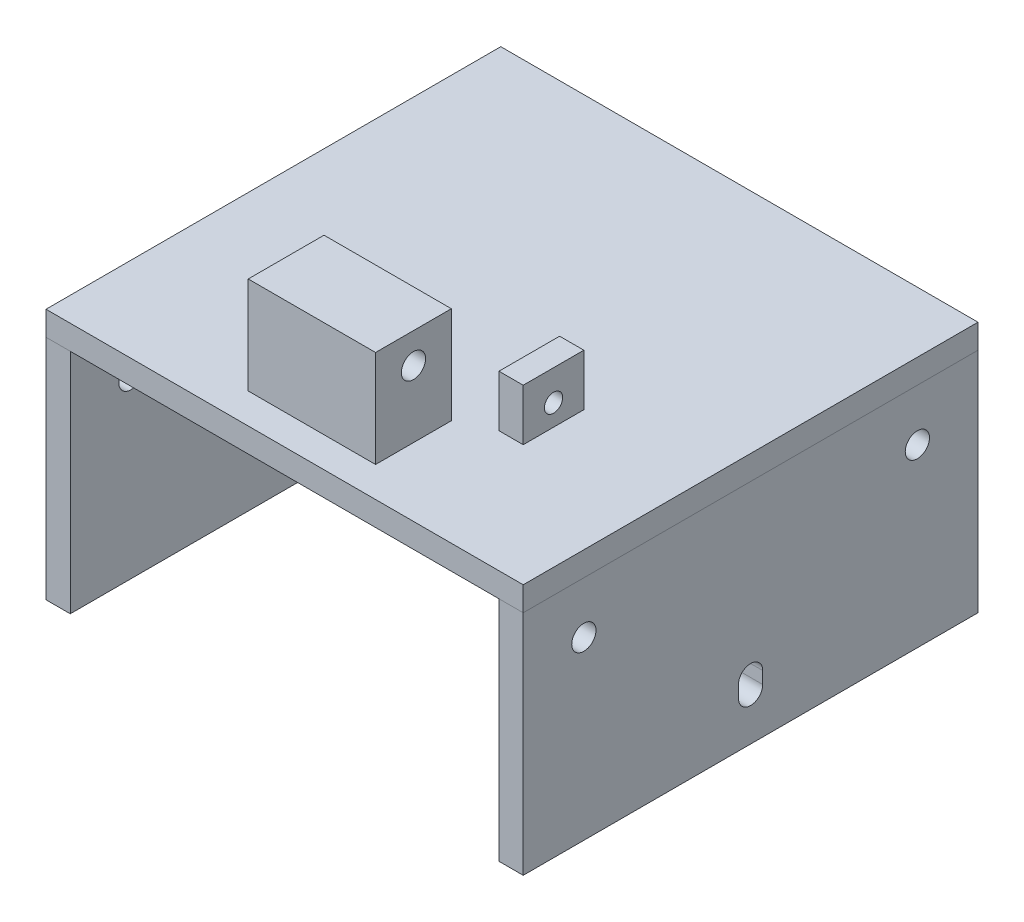
SolidWorks part; units mm, degrees
ref_plane "Front Plane" through (0, 0, 0) normal (0, 0, 1) x (1, 0, 0)
ref_plane "Top Plane" through (0, 0, 0) normal (0, 1, 0) x (1, 0, 0)
ref_plane "Right Plane" through (0, 0, 0) normal (1, 0, 0) x (0, 0, -1)
sketch "Sketch1" plane through (0, 0, 0) normal (0, 0, 1) x (1, 0, 0)
  line L1 (-78.7, -4) -> (78.7, -4)
  line L2 (-78.7, -4) -> (-78.7, 4)
  line L3 (-78.7, 4) -> (78.7, 4)
  line L4 (78.7, -4) -> (78.7, 4)
  line L5 (-78.7, -4) -> (78.7, 4) construction
  line L6 (-78.7, 4) -> (78.7, -4) construction
  point P0 (0, 0)
  dimension "D1" = 8
  dimension "D2" = 157.4
extrude "Boss-Extrude1" add sketch "Sketch1" along normal blind 150
sketch "Sketch2" plane through (0, -4, 0) normal (0, -1, 0) x (1, 0, 0)
  line L0 (-78.7, 0) -> (78.7, 0) construction
  line L1 (-78.7, 150) -> (-70.7, 150)
  line L2 (-78.7, 150) -> (-78.7, 0)
  line L3 (-78.7, 0) -> (-70.7, 0)
  line L4 (-70.7, 150) -> (-70.7, 0)
  line L5 (-78.7, 150) -> (78.7, 150) construction
  line L6 (78.7, 0) -> (70.7, 0)
  line L7 (78.7, 0) -> (78.7, 150)
  line L8 (78.7, 150) -> (70.7, 150)
  line L9 (70.7, 0) -> (70.7, 150)
  dimension "D1" = 8
  dimension "D2" = 8
extrude "Boss-Extrude2" add sketch "Sketch2" along normal blind 75 separate body
sketch "Sketch3" plane through (-78.7, 0, 0) normal (-1, 0, 0) x (0, 0, 1)
  line L0 (150, -4) -> (0, -4) construction
  line L2 (150, -79) -> (150, -4) construction
  line L3 (150, -79) -> (0, -79) construction
  line L4 (79, -60) -> (79, -64)
  line L6 (71, -64) -> (71, -60)
  circle A0 centre (130, -21) radius 4
  circle A1 centre (20, -21) radius 4
  arc A2 (71, -64) -> (79, -64) centre (75, -64) ccw
  arc A3 (79, -60) -> (71, -60) centre (75, -60) ccw
  dimension "D1" = 8
  dimension "D2" = 8
  dimension "D7" = 8
  dimension "D3" = 17
  dimension "D4" = 17
  dimension "D5" = 110
  dimension "D6" = 20
  dimension "D8" = 55
  dimension "D9" = 15
extrude "Cut-Extrude1" cut sketch "Sketch3" against normal through all
sketch "Sketch5" plane through (0, 4, 0) normal (0, 1, 0) x (1, 0, 0)
  line L0 (78.7, -150) -> (-78.7, -150) construction
  line L1 (-22, -115) -> (20, -115)
  line L2 (-22, -115) -> (-22, -140)
  line L3 (-22, -140) -> (20, -140)
  line L4 (20, -115) -> (20, -140)
  line L5 (0, -150) -> (0, -134.8846) construction
  dimension "D1" = 42
  dimension "D2" = 25
  dimension "D3" = 10
  dimension "D4" = 22
extrude "Boss-Extrude3" add sketch "Sketch5" along normal blind 32 separate body
sketch "Sketch7" plane through (20, 0, 0) normal (1, 0, 0) x (0, 0, -1)
  line L0 (-140, 36) -> (-140, 4) construction
  line L1 (-140, 36) -> (-115, 36) construction
  circle A0 centre (-127.5, 26) radius 4
  dimension "D1" = 8
  dimension "D3" = 10
  dimension "D2" = 12.5
extrude "Cut-Extrude2" cut sketch "Sketch7" against normal through all
sketch "Sketch8" plane through (0, 4, 0) normal (0, 1, 0) x (1, 0, 0)
  line L0 (78.7, -150) -> (78.7, 0) construction
  line L1 (38.7, -110) -> (30.7, -110)
  line L2 (38.7, -110) -> (38.7, -90)
  line L3 (38.7, -90) -> (30.7, -90)
  line L4 (30.7, -110) -> (30.7, -90)
  line L5 (78.7, -150) -> (-78.7, -150) construction
  dimension "D1" = 8
  dimension "D2" = 40
  dimension "D3" = 40
  dimension "D4" = 20
extrude "Boss-Extrude4" add sketch "Sketch8" along normal blind 17
sketch "Sketch9" plane through (38.7, 0, 0) normal (1, 0, 0) x (0, 0, -1)
  line L0 (-110, 21) -> (-110, 4) construction
  line L8 (-110, 21) -> (-90, 21) construction
  circle A0 centre (-100, 11) radius 3
  dimension "D1" = 6
  dimension "D2" = 10
  dimension "D3" = 10
extrude "Cut-Extrude3" cut sketch "Sketch9" against normal up to next (8 mm away) contours A0
